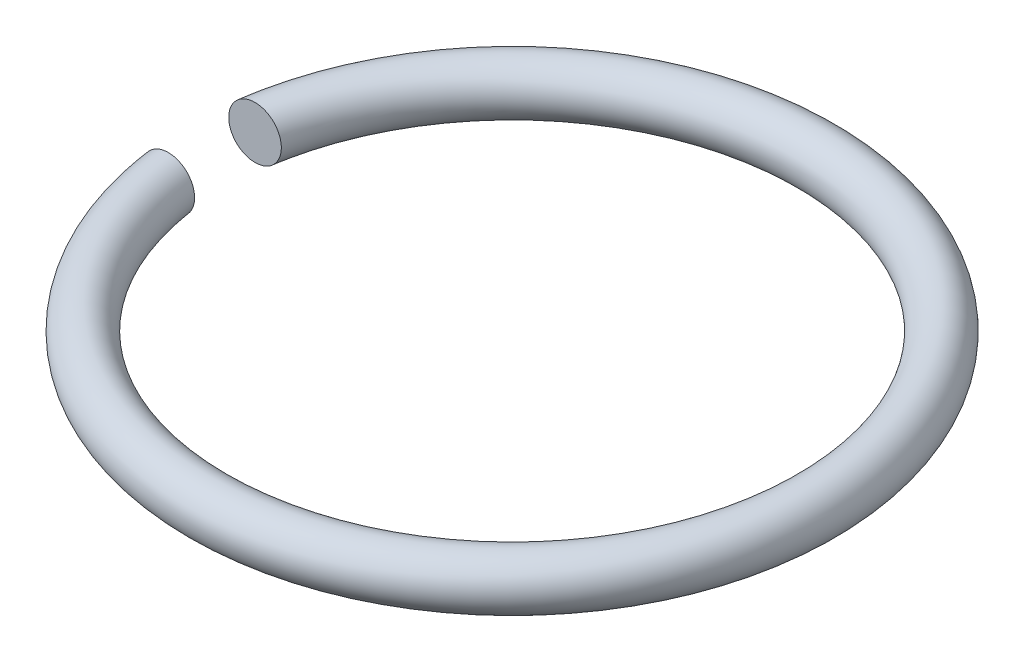
SolidWorks part; units mm, degrees
material "AISI 304"
ref_plane "Спереди" through (0, 0, 0) normal (0, 0, 1) x (1, 0, 0)
ref_plane "Сверху" through (0, 0, 0) normal (0, 1, 0) x (1, 0, 0)
ref_plane "Справа" through (0, 0, 0) normal (1, 0, 0) x (0, 0, -1)
sketch "Эскиз1" plane through (0, 0, 0) normal (0, 0, 1) x (1, 0, 0)
  line L0 (0, 0) -> (0, 5.376) construction
  circle A0 centre (-7, 0.6) radius 0.6
  dimension "D1" = 1.2
  dimension "D2" = 7
  dimension "D3" = 0.6
revolve "Повернуть1" add sketch "Эскиз1" angle 360 about L0
sketch "Эскиз2" plane through (0, 0, 0) normal (0, 1, 0) x (1, 0, 0)
  line L0 (0, 0) -> (-16.7656, 0) construction
  line L1 (-12.162, 1) -> (-2.8072, 1)
  line L2 (-12.162, 1) -> (-12.162, -1)
  line L3 (-12.162, -1) -> (-2.8072, -1)
  line L4 (-2.8072, 1) -> (-2.8072, -1)
  dimension "D1" = 1
  dimension "D2" = 1
extrude "Вырез-Вытянуть1" cut sketch "Эскиз2" against normal through all and the other way through all
ref_plane "Плоскость1" through (0, 0, 0) normal (0, -1, 0) x (-1, 0, 0)
